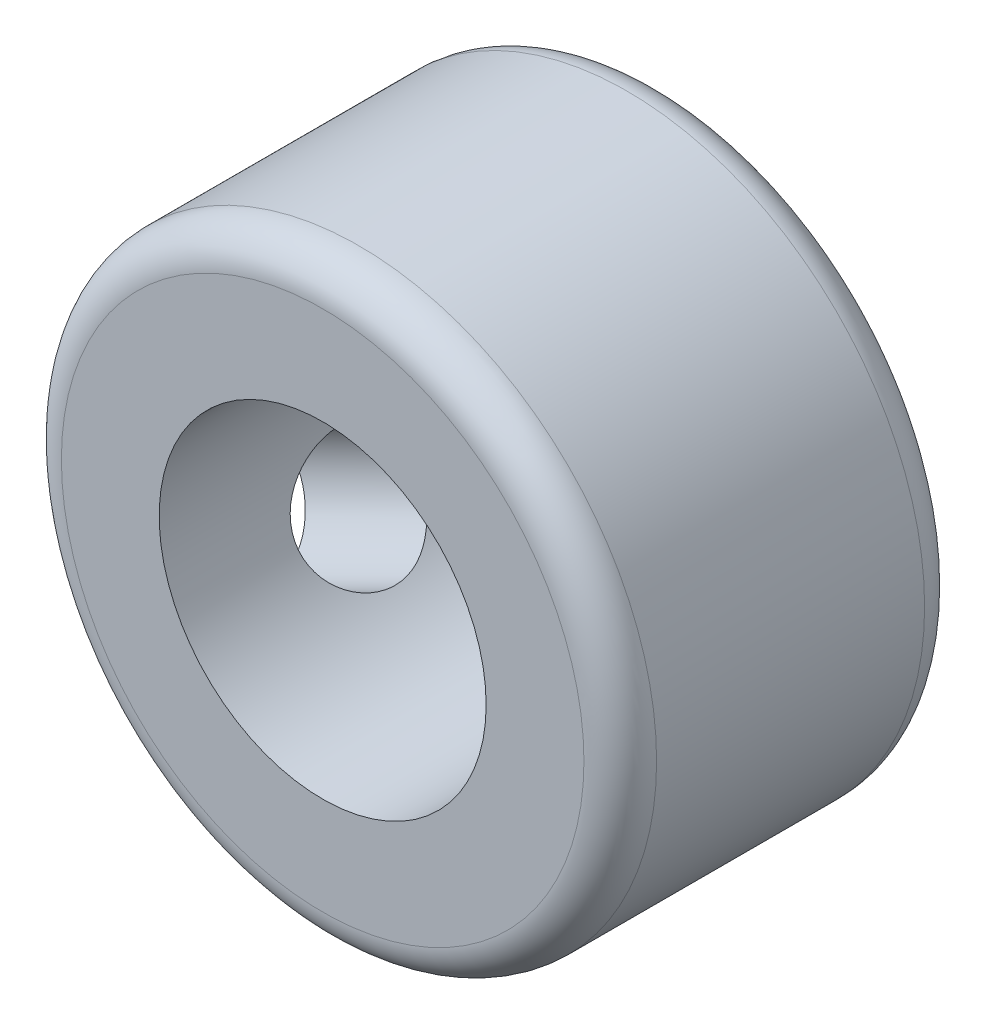
SolidWorks part; units mm, degrees
material "6063-T6"
ref_plane "Plan de face" through (0, 0, 0) normal (0, 0, 1) x (1, 0, 0)
ref_plane "Plan de dessus" through (0, 0, 0) normal (0, 1, 0) x (1, 0, 0)
ref_plane "Plan de droite" through (0, 0, 0) normal (1, 0, 0) x (0, 0, -1)
sketch "Esquisse1" plane through (0, 0, 0) normal (0, 0, 1) x (1, 0, 0)
  circle A0 centre (0, 0) radius 6.242
  circle A1 centre (0, 0) radius 3.429
  dimension "D1" = 12.4841
  dimension "D2" = 6.858
extrude "Boss.-Extru.1" add sketch "Esquisse1" along normal blind 7.145
fillet "Congé1" radius 0.762 2 edges at (6.2421, 0, 0) (6.2421, 0, 7.145)
hole_wizard "Dégagement M21" positions "Esquisse3D1" profile "Esquisse3" hole size "M2" standard "Ansi Metric"
sketch3d "Esquisse3D1"
  point P0 (-5.5947, -2.7681, 3.3596)
sketch "Esquisse3" plane through (-5.5947, -2.7681, 3.3596) normal (0, 0, 1) x (0.4435, -0.8963, 0)
  line L0 (0, 0) -> (0, 2.813)
  line L1 (0, 2.813) -> (1.3, 2.813)
  line L2 (1.3, 2.813) -> (1.3, 0)
  line L5 (1.3, 0) -> (0, 0)
  line L11 (0, -6.35) -> (0, 107.95) construction
  dimension "Diamètre du perçage jusqu'au prochain" = 2.6
  dimension "Profondeur du perçage jusqu'au prochain" = 2.813
